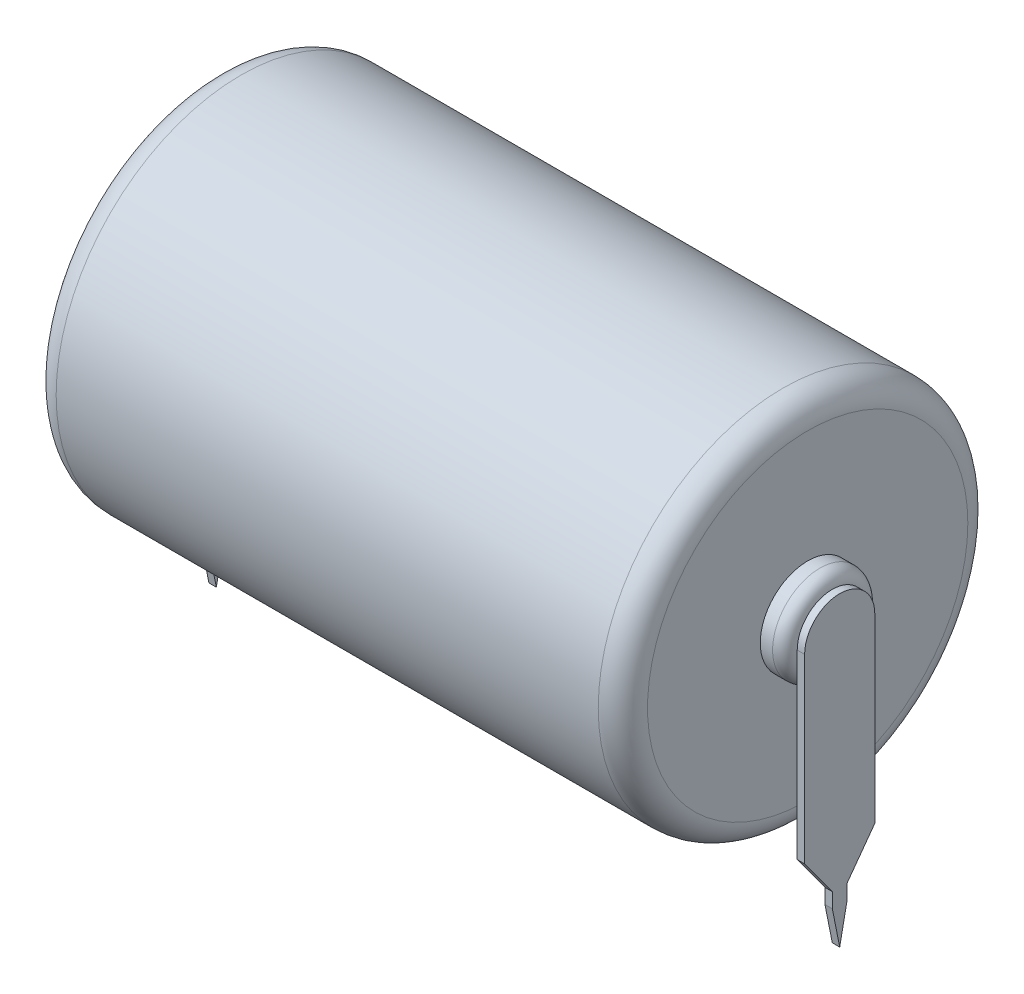
SolidWorks part; units mm, degrees
ref_plane "Front Plane" through (0, 0, 0) normal (0, 0, 1) x (1, 0, 0)
ref_plane "Top Plane" through (0, 0, 0) normal (0, 1, 0) x (1, 0, 0)
ref_plane "Right Plane" through (0, 0, 0) normal (1, 0, 0) x (0, 0, -1)
sketch "Sketch1" plane through (0, 0, 0) normal (1, 0, 0) x (0, 0, -1)
  circle A0 centre (0, 0) radius 7.5
  dimension "D1" = 15
extrude "Boss-Extrude1" add sketch "Sketch1" along normal blind 24
fillet "Fillet1" radius 1 2 edges at (0, 0, -7.5) (24, 0, -7.5)
sketch "Sketch2" plane through (24, 0, 0) normal (1, 0, 0) x (0, 0, -1)
  circle A0 centre (0, 0) radius 1.9243
extrude "Boss-Extrude2" add sketch "Sketch2" along normal blind 1
fillet "Fillet2" radius 0.5 1 edges at (25, 0, -1.9243)
sketch "Sketch3" plane through (0, 0, 0) normal (-1, 0, 0) x (0, 0, 1)
  circle A0 centre (0, 0) radius 5.4775
  circle A1 centre (0, 0) radius 5.1183
extrude "Cut-Extrude1" cut sketch "Sketch3" against normal blind 0.3
sketch "Sketch4" plane through (25, 0, 0) normal (1, 0, 0) x (0, 0, -1)
  line L0 (-1.4243, 0) -> (-1.4243, -7.3635)
  line L1 (1.4243, 0) -> (1.4243, -7.3635)
  line L3 (-1.4243, -7.3635) -> (-0.5119, -8.6104)
  line L4 (1.4243, -7.3635) -> (0.5205, -8.5986)
  line L5 (-0.5119, -8.6104) -> (-0.3, -8.9)
  line L6 (-0.3, -8.9) -> (-0.3, -9.5)
  line L7 (-0.3, -9.5) -> (0, -11)
  line L8 (0.5205, -8.5986) -> (0.3, -8.9)
  line L9 (0.3, -8.9) -> (0.3, -9.5)
  line L10 (0.3, -9.5) -> (0, -11)
  arc A0 (1.4243, 0) -> (-1.4243, 0) centre (0, 0) ccw
  circle A1 centre (0, 0) radius 7.5 construction
  point P9 (0, 0)
  point P19 (0.1294, -0.0689)
  dimension "D5" = 2.8485
  dimension "D1" = 1.5365
  dimension "D2" = 3.6365
  dimension "D3" = 1.1243
  dimension "D4" = 1.1243
  dimension "D6" = 1.5365
  dimension "D7" = 1.5
  dimension "D8" = 1.5
extrude "Boss-Extrude3" add sketch "Sketch4" along normal blind 0.3
sketch "Sketch5" plane through (0, 0, 0) normal (-1, 0, 0) x (0, 0, 1)
  line L10 (-0.3, -8.9) -> (-0.3, -9.5)
  line L11 (-0.3, -9.5) -> (0, -11)
  line L12 (0, -11) -> (0.3, -9.5)
  line L13 (0.3, -9.5) -> (0.3, -8.9)
  line L14 (0.3, -8.9) -> (0.5119, -8.6104)
  line L15 (0.5119, -8.6104) -> (1.4243, -7.3635)
  line L16 (1.4243, -7.3635) -> (1.4243, 0)
  line L17 (-1.4243, 0) -> (-1.4243, -7.3635)
  line L18 (-1.4243, -7.3635) -> (-0.5205, -8.5986)
  line L19 (-0.5205, -8.5986) -> (-0.3, -8.9)
  line L20 (-0.3, -8.9) -> (-0.3, -9.5)
  line L21 (-0.3, -9.5) -> (0, -11)
  line L22 (0, -11) -> (0.3, -9.5)
  line L23 (0.3, -9.5) -> (0.3, -8.9)
  line L24 (0.3, -8.9) -> (0.5119, -8.6104)
  line L25 (0.5119, -8.6104) -> (1.4243, -7.3635)
  line L26 (1.4243, -7.3635) -> (1.4243, 0)
  line L27 (-1.4243, 0) -> (-1.4243, -7.3635)
  line L28 (-1.4243, -7.3635) -> (-0.5205, -8.5986)
  line L29 (-0.5205, -8.5986) -> (-0.3, -8.9)
  arc A1 (1.4243, 0) -> (-1.4243, 0) centre (0, 0) ccw
  arc A2 (1.4243, 0) -> (-1.4243, 0) centre (0, 0) ccw
  dimension "D1" = 0
extrude "Boss-Extrude4" add sketch "Sketch5" along normal blind 0.3
